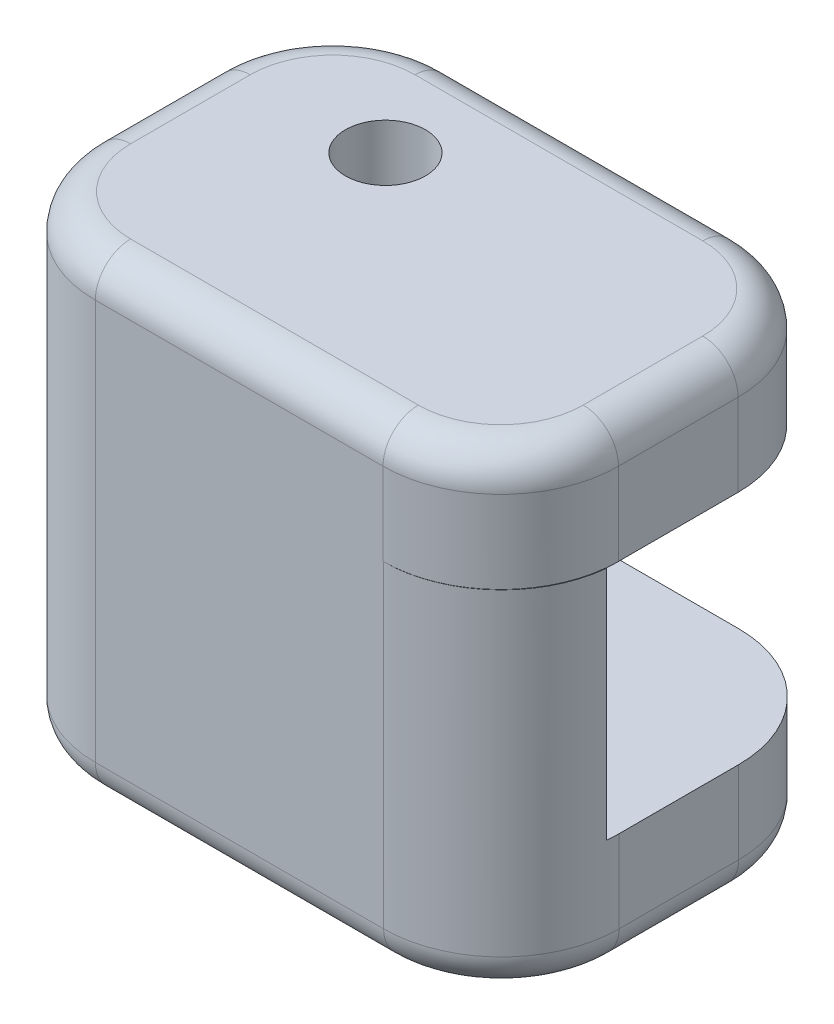
SolidWorks part; units mm, degrees
ref_plane "Front Plane" through (0, 0, 0) normal (0, 0, 1) x (1, 0, 0)
ref_plane "Top Plane" through (0, 0, 0) normal (0, 1, 0) x (1, 0, 0)
ref_plane "Right Plane" through (0, 0, 0) normal (1, 0, 0) x (0, 0, -1)
sketch "Sketch1" plane through (0, 0, 0) normal (0, 1, 0) x (1, 0, 0)
  line L0 (0, 0) -> (10, 0) construction
  line L1 (0, 5) -> (10, 5)
  line L4 (15, 0) -> (15, -5.0781)
  line L5 (-2.2415, -10.0781) -> (10, -10.0781)
  line L6 (0, 5) -> (-2.2415, 5)
  line L7 (-7.2415, 0) -> (-7.2415, -5.0781)
  arc A1 (15, 0) -> (10, 5) centre (10, 0) ccw
  arc A3 (15, -5.0781) -> (10, -10.0781) centre (10, -5.0781) cw
  arc A4 (-2.2415, -10.0781) -> (-7.2415, -5.0781) centre (-2.2415, -5.0781) cw
  arc A5 (-2.2415, 5) -> (-7.2415, 0) centre (-2.2415, 0) ccw
  circle A7 centre (0, 0) radius 1.7
  point P3 (5, 0)
  dimension "D1" = 10
  dimension "D2" = 5
  dimension "D3" = 5
  dimension "D4" = 5
  dimension "D5" = 5
  dimension "D6" = 3.4
extrude "Boss-Extrude1" add sketch "Sketch1" along normal blind 5
sketch "Sketch2" plane through (0, 5, 0) normal (0, 1, 0) x (1, 0, 0)
  line L0 (0, 0) -> (10, 0) construction
  line L3 (-5.5781, 0) -> (-7.2415, 0)
  line L4 (-7.2415, 0) -> (-7.2415, -5.0781)
  line L5 (-2.2415, -10.0781) -> (10, -10.0781)
  line L8 (-2.2415, -10.0781) -> (10, -10.0781) construction
  line L9 (0, 0) -> (10, 0) construction
  line L11 (0, -5.5781) -> (14.9749, -5.5781)
  arc A4 (-7.2415, -5.0781) -> (-2.2415, -10.0781) centre (-2.2415, -5.0781) ccw
  arc A5 (-5.5781, 0) -> (0, -5.5781) centre (0, 0) ccw
  arc A9 (10, -10.0781) -> (15, -5.0781) centre (10, -5.0781) ccw construction
  arc A10 (10, -10.0781) -> (14.9749, -5.5781) centre (10, -5.0781) ccw
  point P3 (5, 0)
  point P4 (5, 0)
  dimension "D1" = 4.5
extrude "Boss-Extrude2" add sketch "Sketch2" along normal blind 10
sketch "Sketch3" plane through (0, 15, 0) normal (0, 1, 0) x (1, 0, 0)
  line L1 (14.9749, -5.5781) -> (-7.2415, -5.5781)
  line L2 (14.9749, -5.5781) -> (14.9749, 0)
  line L3 (14.9749, 0) -> (-7.2415, 0)
  line L4 (-7.2415, -5.5781) -> (-7.2415, 0)
extrude "Cut-Extrude1" cut sketch "Sketch3" against normal blind 7
sketch "Sketch4" plane through (0, 15, 0) normal (0, 1, 0) x (1, 0, 0)
  line L0 (-2.2415, 5) -> (-7.2415, 5) construction
  line L1 (-7.2415, 0) -> (-7.2415, 5) construction
  line L2 (10, -10.0781) -> (14.9749, -10.0781) construction
  line L3 (-2.2415, 5) -> (9.9749, 5)
  line L4 (-7.2415, 0) -> (-7.2415, -5.0781)
  line L5 (-2.2415, -10.0781) -> (9.9749, -10.0781)
  line L6 (14.9749, 0) -> (14.9749, -5.0781)
  line L7 (14.9749, -5.5781) -> (14.9749, -10.0781) construction
  circle A0 centre (0, 0) radius 1.7
  circle A1 centre (0, 0) radius 1.7 construction
  arc A2 (9.9749, -10.0781) -> (14.9749, -5.0781) centre (9.9749, -5.0781) ccw
  arc A3 (-7.2415, -5.0781) -> (-2.2415, -10.0781) centre (-2.2415, -5.0781) ccw
  arc A4 (-2.2415, 5) -> (-7.2415, 0) centre (-2.2415, 0) ccw
  arc A5 (9.9749, 5) -> (14.9749, 0) centre (9.9749, 0) cw
  dimension "D1" = 5
extrude "Boss-Extrude3" add sketch "Sketch4" along normal blind 5
sketch "Sketch5" plane through (0, 0, 0) normal (0, -1, 0) x (1, 0, 0)
  line L1 (3.2332, 0) -> (1.6166, 2.8)
  line L2 (1.6166, 2.8) -> (-1.6166, 2.8)
  line L3 (-1.6166, 2.8) -> (-3.2332, 0)
  line L4 (-3.2332, 0) -> (-1.6166, -2.8)
  line L5 (-1.6166, -2.8) -> (1.6166, -2.8)
  line L6 (1.6166, -2.8) -> (3.2332, 0)
  circle A0 centre (0, 0) radius 2.8 construction
  dimension "D1" = 5.6
  dimension "D2" = 2.8
extrude "Cut-Extrude2" cut sketch "Sketch5" against normal blind 2.6
fillet "Fillet1" radius 1.5 16 edges at (-7.2415, 20, 2.5391) (-5.777, 20, -3.5355) (3.8667, 20, -5) (13.5105, 20, -3.5355) (14.9749, 20, 2.5391) (13.5105, 20, 8.6137) (3.8667, 20, 10.0781) (-5.777, 0, -3.5355) (3.8793, 0, -5) (13.5355, 0, -3.5355) (15, 0, 2.5391) (13.5355, 0, 8.6137) (3.8793, 0, 10.0781) (-5.777, 0, 8.6137) (-5.777, 20, 8.6137) (-7.2415, 0, 2.5391)
